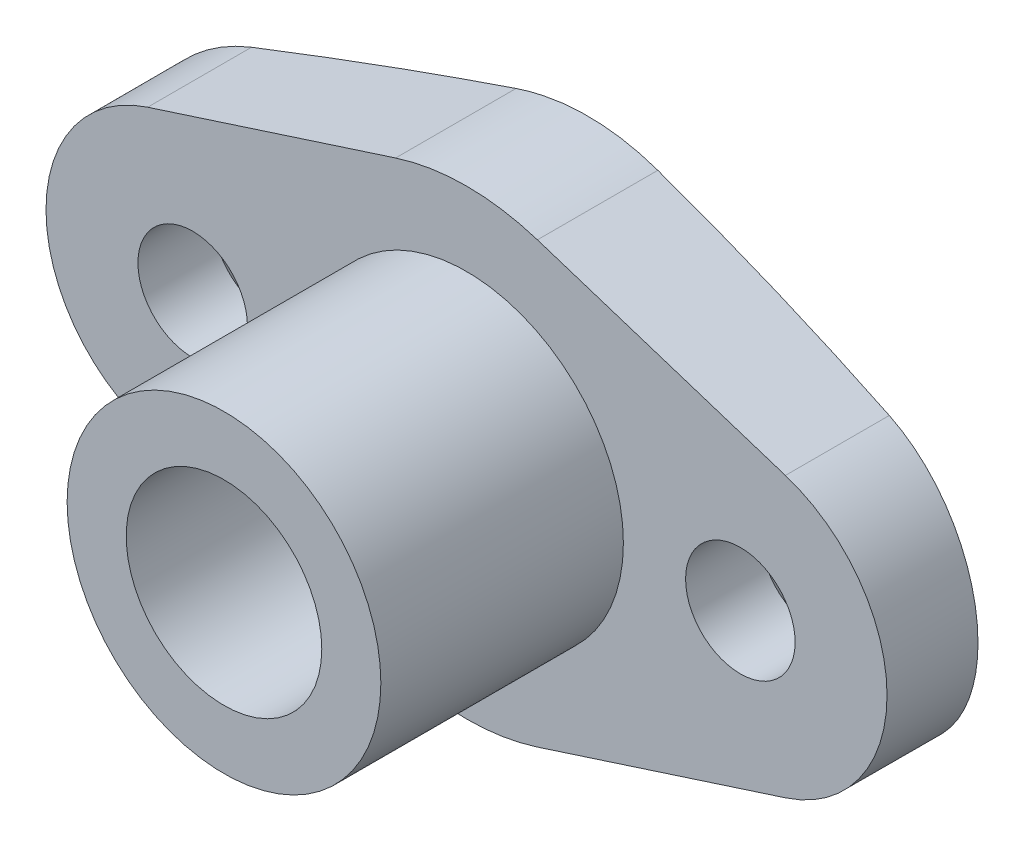
SolidWorks part; units mm, degrees
ref_plane "Front Plane" through (0, 0, 0) normal (0, 0, 1) x (1, 0, 0)
ref_plane "Top Plane" through (0, 0, 0) normal (0, 1, 0) x (1, 0, 0)
ref_plane "Right Plane" through (0, 0, 0) normal (1, 0, 0) x (0, 0, -1)
sketch "Sketch1" plane through (0, 0, 0) normal (0, 0, 1) x (1, 0, 0)
  line L0 (-10.3528, 4.5323) -> (-2.3014, 7.1308)
  line L1 (2.3014, 7.1308) -> (10.3528, 4.5323)
  line L2 (10.3528, -4.5323) -> (2.3014, -7.1308)
  line L3 (-2.3014, -7.1308) -> (-10.3528, -4.5323)
  line L4 (-8.89, 0) -> (8.89, 0) construction
  line L5 (-13.6525, 0) -> (13.6525, 0) construction
  circle A0 centre (0, 0) radius 7.493
  circle A1 centre (8.89, 0) radius 1.778
  circle A2 centre (-8.89, 0) radius 1.778
  arc A3 (-10.3528, 4.5323) -> (-10.3528, -4.5323) centre (-8.89, 0) ccw
  arc A4 (10.3528, -4.5323) -> (10.3528, 4.5323) centre (8.89, 0) ccw
  circle A5 centre (0, 0) radius 3.175
  dimension "shaft dia" = 6.35
sketch "Sketch2" plane through (0, 0, 0) normal (0, 1, 0) x (1, 0, 0)
  line L0 (0, 0) -> (0, -11.811) construction
  point P3 (0, -3.937)
sketch "Sketch3" plane through (0, 0, 0) normal (0, 0, 1) x (1, 0, 0)
  line L0 (2.3014, 7.1308) -> (10.3528, 4.5323) construction
  line L1 (10.3528, -4.5323) -> (2.3014, -7.1308) construction
  line L2 (-10.3528, 4.5323) -> (-2.3014, 7.1308) construction
  line L3 (-2.3014, -7.1308) -> (-10.3528, -4.5323) construction
  line L4 (2.3014, 7.1308) -> (10.3528, 4.5323)
  line L5 (10.3528, -4.5323) -> (2.3014, -7.1308)
  line L6 (-10.3528, 4.5323) -> (-2.3014, 7.1308)
  line L7 (-2.3014, -7.1308) -> (-10.3528, -4.5323)
  arc A0 (10.3528, -4.5323) -> (10.3528, 4.5323) centre (8.89, 0) ccw construction
  arc A1 (-10.3528, 4.5323) -> (-10.3528, -4.5323) centre (-8.89, 0) ccw construction
  arc A2 (10.3528, -4.5323) -> (10.3528, 4.5323) centre (8.89, 0) ccw
  arc A3 (-10.3528, 4.5323) -> (-10.3528, -4.5323) centre (-8.89, 0) ccw
  arc A4 (-2.3014, -7.1308) -> (2.3014, -7.1308) centre (0, 0) ccw
  circle A5 centre (-8.89, 0) radius 1.778
  circle A6 centre (-8.89, 0) radius 1.778
  circle A7 centre (8.89, 0) radius 1.778
  circle A8 centre (8.89, 0) radius 1.778
  circle A9 centre (0, 0) radius 7.493
  arc A10 (2.3014, 7.1308) -> (-2.3014, 7.1308) centre (0, 0) ccw
  circle A11 centre (0, 0) radius 3.175
  circle A12 centre (0, 0) radius 3.175 construction
  dimension "D1" = 0
  dimension "D2" = 0
  dimension "D3" = 0
  dimension "D4" = 0
extrude "Extrude1" add sketch "Sketch3" along normal up to vertex (3.937 mm away) up to point (0, 0, 3.937)
sketch "Sketch4" plane through (0, 0, 3.937) normal (0, 0, 1) x (1, 0, 0)
  circle A0 centre (0, 0) radius 3.175 construction
  circle A1 centre (0, 0) radius 3.175
  circle A2 centre (0, 0) radius 5.0927
  dimension "dd" = 10.1854
extrude "Extrude2" add sketch "Sketch4" along normal up to vertex (7.874 mm away) up to point (0, 0, 11.811)
sketch "Sketch5" plane through (0, 0, 0) normal (0, 0, -1) x (-1, 0, 0)
  circle A0 centre (-8.89, 0) radius 3.556
  circle A1 centre (8.89, 0) radius 3.556
  dimension "D1" = 7.112
extrude "Cut-Extrude1" cut sketch "Sketch5" against normal through all draft 50
sketch "Sketch6" plane through (0, 0, 0) normal (0, 1, 0) x (1, 0, 0)
  line L0 (13.6525, -0.9842) -> (13.6525, 0.508)
  line L1 (13.6525, 0.508) -> (-13.6525, 0.508)
  line L2 (-13.6525, 0.508) -> (-13.6525, -0.9842)
  line L3 (10.3528, 0) -> (13.6525, 0) construction
  arc A0 (-13.6525, -0.9842) -> (13.6525, -0.9842) centre (0, -95.1788) cw
  dimension "D1" = 0.508
  dimension "D2" = 0.9842
extrude "Cut-Extrude2" cut sketch "Sketch6" against normal mid plane 76.2
equation "\"D1@Sketch5\" = \"F@Sketch1\"*2"
equation "\"D2@Sketch6\" = \"G@Sketch2\"/4"
